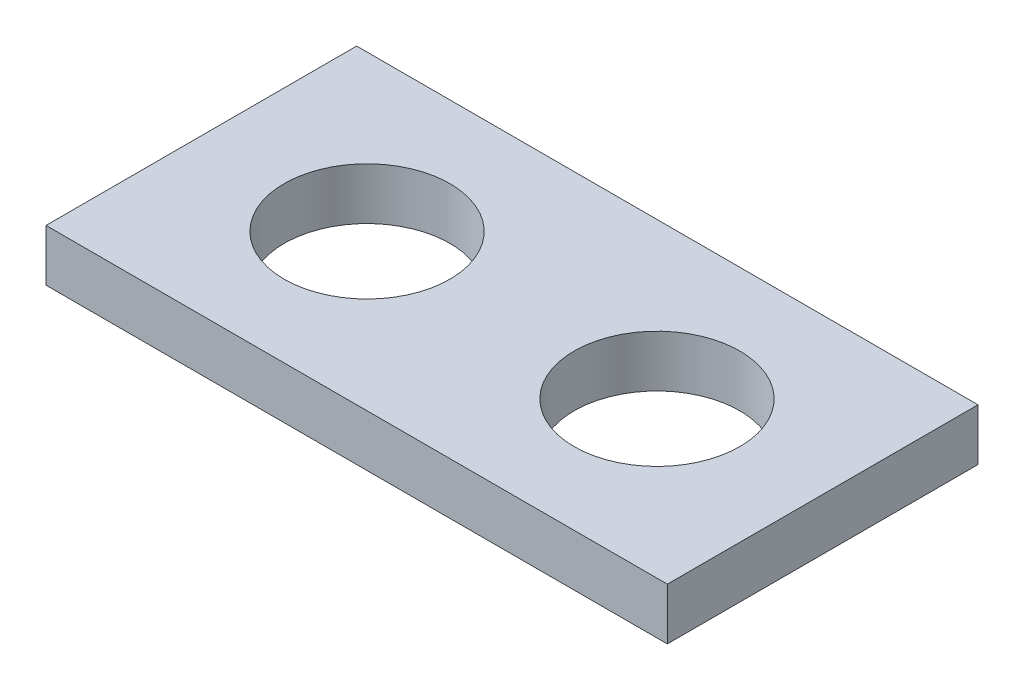
SolidWorks part; units mm, degrees
ref_plane "Front Plane" through (0, 0, 0) normal (0, 0, 1) x (1, 0, 0)
ref_plane "Top Plane" through (0, 0, 0) normal (0, 1, 0) x (1, 0, 0)
ref_plane "Right Plane" through (0, 0, 0) normal (1, 0, 0) x (0, 0, -1)
sketch "Sketch2" plane through (0, 0, 0) normal (0, 1, 0) x (1, 0, 0)
  line L1 (0, 0) -> (30, 0)
  line L2 (0, 0) -> (0, 15)
  line L3 (0, 15) -> (30, 15)
  line L4 (30, 0) -> (30, 15)
  dimension "D1" = 15
  dimension "D2" = 30
extrude "Boss-Extrude1" add sketch "Sketch2" along normal blind 2.5
sketch "Sketch4" plane through (0, 2.5, 0) normal (0, 1, 0) x (1, 0, 0)
  line L0 (30, 0) -> (30, 15) construction
  line L1 (0, 0) -> (30, 0) construction
  circle A0 centre (22, 7.5) radius 4
  circle A1 centre (8, 7.5) radius 4
  dimension "D1" = 8
  dimension "D2" = 8
  dimension "D4" = 8
  dimension "D5" = 7.5
  dimension "D3" = 14
extrude "Cut-Extrude1" cut sketch "Sketch4" against normal through all both
